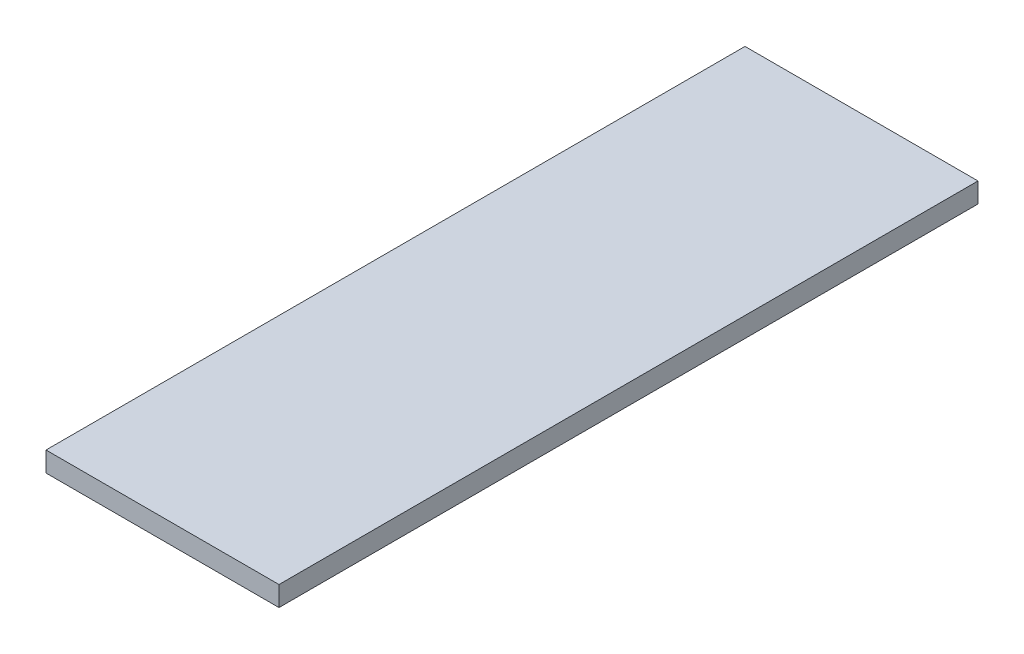
SolidWorks part; units mm, degrees
ref_plane "Front Plane" through (0, 0, 0) normal (0, 0, 1) x (1, 0, 0)
ref_plane "Top Plane" through (0, 0, 0) normal (0, 1, 0) x (1, 0, 0)
ref_plane "Right Plane" through (0, 0, 0) normal (1, 0, 0) x (0, 0, -1)
sketch "Sketch1" plane through (0, 0, 0) normal (0, 1, 0) x (1, 0, 0)
  line L1 (17.5, -52.5) -> (-17.5, -52.5)
  line L2 (17.5, -52.5) -> (17.5, 52.5)
  line L3 (17.5, 52.5) -> (-17.5, 52.5)
  line L4 (-17.5, -52.5) -> (-17.5, 52.5)
  line L5 (17.5, -52.5) -> (-17.5, 52.5) construction
  line L6 (17.5, 52.5) -> (-17.5, -52.5) construction
  point P0 (0, 0)
  dimension "D1" = 105
  dimension "D2" = 35
extrude "Boss-Extrude1" add sketch "Sketch1" along normal blind 3
